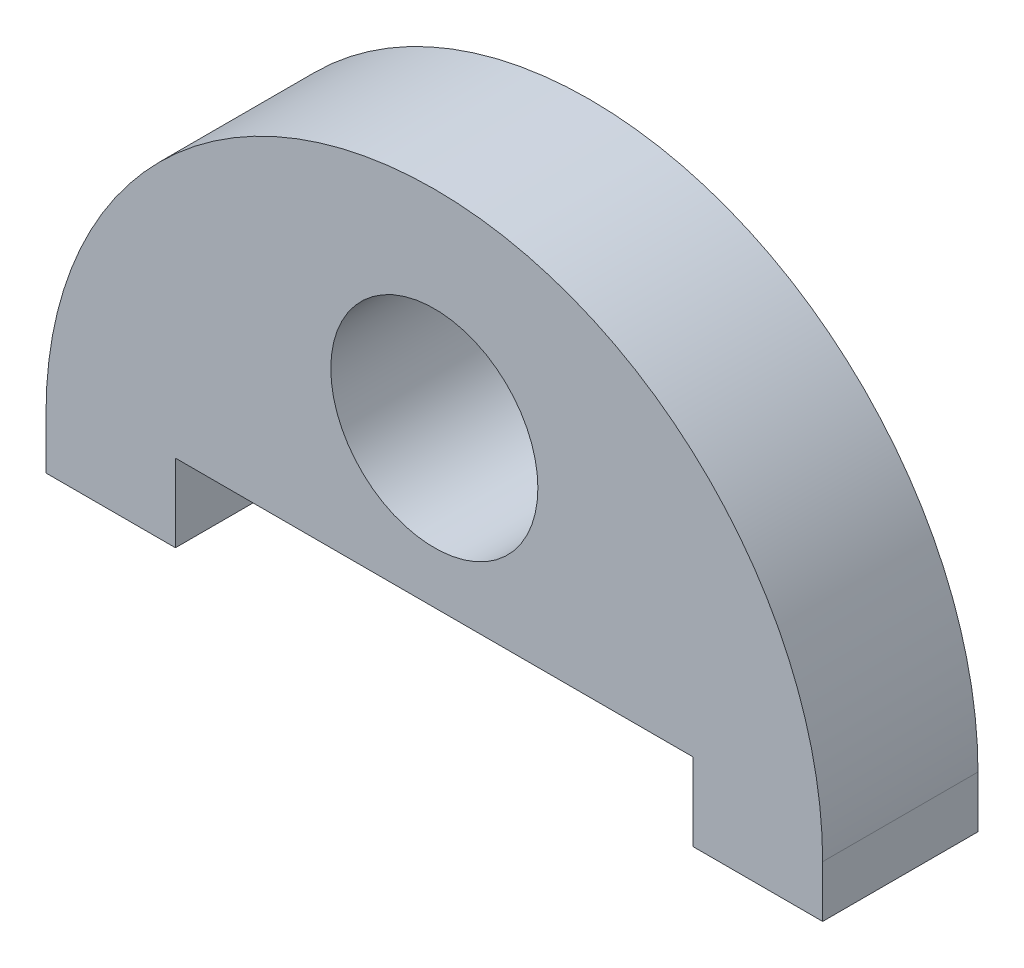
SolidWorks part; units mm, degrees
ref_plane "Front Plane" through (0, 0, 0) normal (0, 0, 1) x (1, 0, 0)
ref_plane "Top Plane" through (0, 0, 0) normal (0, 1, 0) x (1, 0, 0)
ref_plane "Right Plane" through (0, 0, 0) normal (1, 0, 0) x (0, 0, -1)
sketch "Sketch1" plane through (0, 0, 0) normal (0, 0, 1) x (1, 0, 0)
  line L0 (0, 0) -> (5, 0)
  line L1 (5, 0) -> (5, 3)
  line L2 (5, 3) -> (25, 3)
  line L3 (25, 3) -> (25, 0)
  line L4 (25, 0) -> (30, 0)
  line L5 (30, 0) -> (30, 2)
  line L6 (0, 0) -> (0, 2)
  arc A0 (0, 2) -> (30, 2) centre (15, 2) cw
  circle A1 centre (15, 9) radius 4
  dimension "D4" = 2
  dimension "D5" = 8
  dimension "D6" = 6
  dimension "D7" = 15
  dimension "D1" = 3
  dimension "D2" = 5
  dimension "D3" = 30
extrude "Boss-Extrude1" add sketch "Sketch1" along normal blind 6
